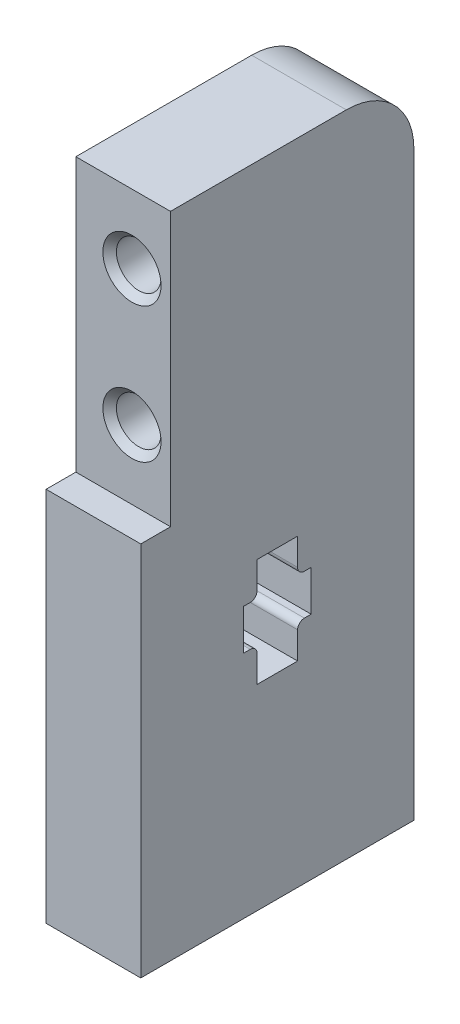
SolidWorks part; units mm, degrees
ref_plane "Alzado" through (0, 0, 0) normal (0, 0, 1) x (1, 0, 0)
ref_plane "Planta" through (0, 0, 0) normal (0, 1, 0) x (1, 0, 0)
ref_plane "Vista lateral" through (0, 0, 0) normal (1, 0, 0) x (0, 0, -1)
sketch "Croquis1" plane through (0, 0, 0) normal (1, 0, 0) x (0, 0, -1)
  line L1 (0, 0) -> (20.2, 0)
  line L2 (0, 0) -> (0, 48)
  line L3 (0, 48) -> (20.2, 48)
  line L4 (20.2, 0) -> (20.2, 48)
extrude "Saliente-Extruir1" add sketch "Croquis1" along normal blind 7
sketch "Croquis2" plane through (0, 0, 0) normal (0, 0, 1) x (1, 0, 0)
  line L0 (7, 48) -> (7, 0) construction
  line L1 (0, 48) -> (7, 48)
  line L2 (0, 48) -> (0, 27.8)
  line L3 (0, 27.8) -> (7, 27.8)
  line L4 (7, 48) -> (7, 27.8)
extrude "Cortar-Extruir1" cut sketch "Croquis2" against normal blind 2.2
sketch "Croquis3" plane through (0, 0, 0) normal (0, -1, 0) x (1, 0, 0)
  line L0 (0, 0) -> (1.9, 0)
  line L2 (7, 0) -> (0, 0) construction
  line L4 (3.5, 0) -> (3.5, -2.85)
  line L6 (1.9, 0) -> (1.9, -2.85)
  line L7 (1.9, -2.85) -> (3.5, -2.85)
  line L9 (3.5, -2.85) -> (3.468, -2.8574)
  line L10 (1.9, -17.35) -> (0, -17.35)
  line L11 (7, -20.2) -> (0, -20.2) construction
  line L12 (1.9, -20.2) -> (1.9, -17.35)
  line L13 (0, 0) -> (0, -20.2) construction
  line L14 (1.9, -17.35) -> (1.9, -15.1)
  line L15 (1.9, -15.1) -> (4.15, -15.1)
  line L16 (1.9, -2.85) -> (1.9, -5.1)
  line L17 (1.9, -5.1) -> (4.15, -5.1)
  circle A0 centre (4.15, -5.1) radius 2.25
  circle A1 centre (4.15, -15.1) radius 2.25
  circle A2 centre (4.15, -5.1) radius 1.62
  circle A3 centre (4.15, -15.1) radius 1.65
extrude "Cortar-Extruir2" cut sketch "Croquis3" against normal blind 15
sketch "Croquis4" plane through (0, 0, -2.2) normal (0, 0, 1) x (1, 0, 0)
  line L0 (0, 48) -> (1.9, 48)
  line L1 (1.9, 45.15) -> (3.5, 45.15)
  line L2 (7, 48) -> (0, 48) construction
  line L3 (3.5, 48) -> (3.5, 45.15)
  line L4 (1.9, 48) -> (1.9, 45.15)
  line L5 (1.9, 45.15) -> (1.9, 42.9)
  line L6 (1.9, 42.9) -> (4.15, 42.9)
  line L7 (0, 37.9) -> (7, 37.9)
  line L8 (0, 48) -> (0, 27.8) construction
  line L9 (7, 27.8) -> (7, 48) construction
  line L10 (1.9, 32.9) -> (4.15, 32.9)
  line L11 (1.9, 30.65) -> (1.9, 32.9)
  line L12 (1.9, 27.8) -> (1.9, 30.65)
  line L13 (3.5, 27.8) -> (3.5, 30.65)
  line L14 (1.9, 30.65) -> (3.5, 30.65)
  line L15 (0, 27.8) -> (1.9, 27.8)
  circle A0 centre (4.15, 42.9) radius 2.25
  circle A1 centre (4.15, 32.9) radius 2.25
  circle A2 centre (4.15, 32.9) radius 1.65
  circle A3 centre (4.15, 42.9) radius 1.65
extrude "Cortar-Extruir3" cut sketch "Croquis4" against normal blind 15
chamfer "Chaflán1" distance 0.5 angle 45 4 edges at (4.15, 0, -16.75) (4.15, 0, -6.72) (5.8, 32.9, -2.2) (5.8, 42.9, -2.2)
fillet "Redondeo1" radius 5 1 edges at (3.5, 48, -20.2)
sketch "Croquis5" plane through (7, 0, 0) normal (1, 0, 0) x (0, 0, -1)
  line L0 (7.6, 17) -> (12.6, 17)
  line L5 (12.6, 20) -> (7.6, 20)
  line L6 (7.6, 20) -> (7.6, 17)
  line L7 (12.6, 20) -> (12.6, 17)
extrude "Cortar-Extruir4" cut sketch "Croquis5" against normal blind 7
sketch "Croquis6" plane through (7, 0, 0) normal (1, 0, 0) x (0, 0, -1)
  line L1 (12.6, 20) -> (7.6, 20) construction
  line L2 (8.6, 22.5) -> (11.6, 22.5)
  line L3 (11.6, 22.5) -> (11.6, 20)
  line L4 (11.6, 20) -> (8.6, 20)
  line L5 (8.6, 22.5) -> (8.6, 20)
  line L8 (11.6, 17) -> (8.6, 17)
  line L9 (11.6, 14.5) -> (11.6, 17)
  line L10 (8.6, 14.5) -> (8.6, 17)
  line L11 (8.6, 14.5) -> (11.6, 14.5)
extrude "Cortar-Extruir5" cut sketch "Croquis6" against normal blind 7
fillet "Redondeo2" radius 0.5 4 edges at (3.5, 17, -8.6) (3.5, 17, -11.6) (3.5, 20, -11.6) (3.5, 20, -8.6)
